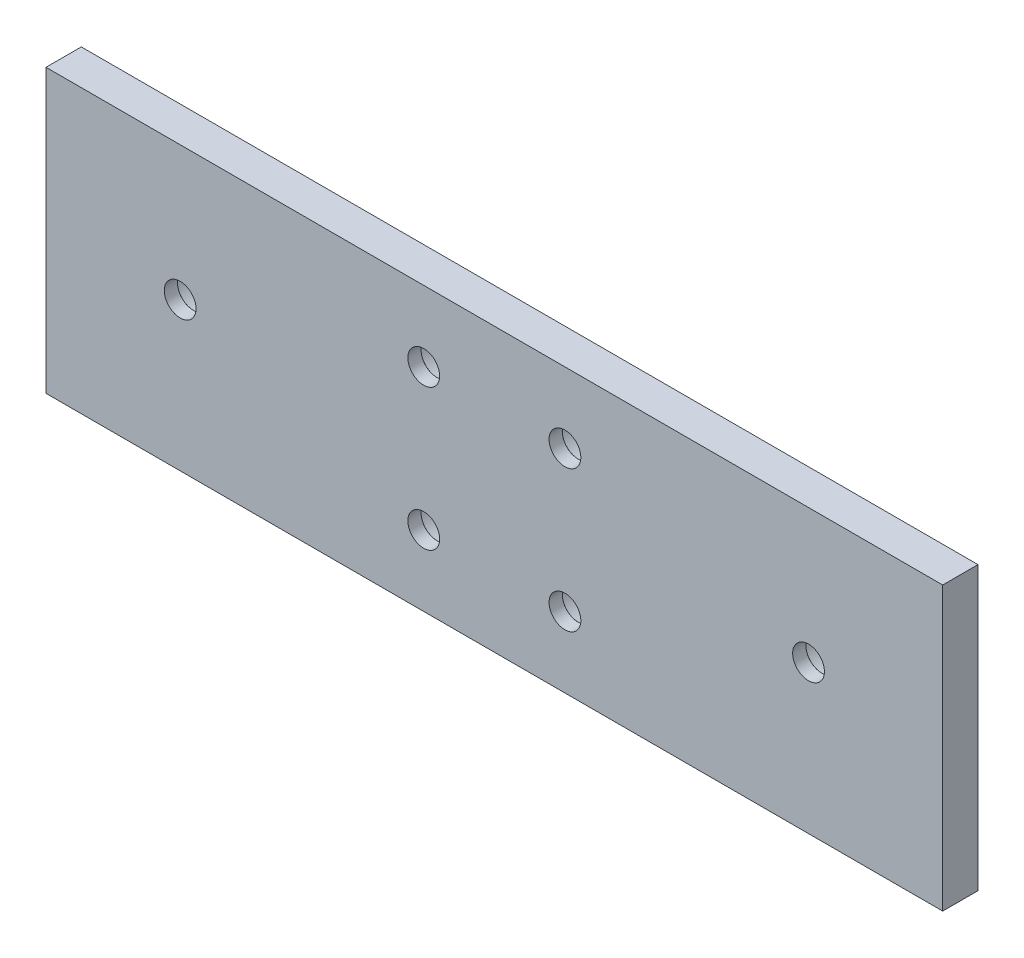
SolidWorks part; units mm, degrees
ref_plane "Plan de face" through (0, 0, 0) normal (0, 0, 1) x (1, 0, 0)
ref_plane "Plan de dessus" through (0, 0, 0) normal (0, 1, 0) x (1, 0, 0)
ref_plane "Plan de droite" through (0, 0, 0) normal (1, 0, 0) x (0, 0, -1)
sketch "Esquisse1" plane through (0, 0, 0) normal (0, 0, 1) x (1, 0, 0)
  line L1 (-63.5, -20) -> (63.5, -20)
  line L2 (-63.5, -20) -> (-63.5, 20)
  line L3 (-63.5, 20) -> (63.5, 20)
  line L4 (63.5, -20) -> (63.5, 20)
  line L5 (-63.5, -20) -> (63.5, 20) construction
  line L6 (-63.5, 20) -> (63.5, -20) construction
  point P0 (0, 0)
  dimension "D1" = 40
  dimension "D2" = 127
extrude "Boss.-Extru.1" add sketch "Esquisse1" along normal blind 5
hole_wizard "Chambrage pour vis à tête ronde bombée M41" positions "Esquisse3" profile "Esquisse2" counterbore size "M4" standard "Ansi Metric" end condition through all
sketch "Esquisse3" plane through (0, 0, 0) normal (0, 0, -1) x (-1, 0, 0)
  point P0 (-44.5, 1)
  point P3 (44.5, 1)
sketch "Esquisse2" plane through (44.5, 1, 0) normal (1, 0, 0) x (0, 1, 0)
  line L0 (0, 0) -> (0, 5)
  line L1 (0, 5) -> (2.25, 5)
  line L2 (2.25, 3.125) -> (2.25, 5)
  line L3 (2.25, 3.125) -> (2.275, 3.1)
  line L4 (2.275, 3.1) -> (4.5, 3.1)
  line L5 (4.5, 3.1) -> (4.5, 0)
  line L7 (0, 0) -> (4.5, 0)
  line L9 (-2.25, 3.125) -> (-2.275, 3.1) construction
  line L11 (0, -6.35) -> (0, 107.95) construction
  dimension "Diamètre du perçage jusqu'au prochain" = 4.5
  dimension "Profondeur du perçage jusqu'au prochain" = 5
  dimension "Diamètre du chambrage" = 9
  dimension "Profondeur du chambrage" = 3.1
  dimension "Diamètre du fraisage milieu" = 4.55
  dimension "Angle du fraisage milieu" = 90
hole_wizard "Dégagement M21" positions "Esquisse5" profile "Esquisse4" hole size "M2" standard "JIS" end condition through all
sketch "Esquisse5" plane through (0, 0, 5) normal (0, 0, 1) x (1, 0, 0)
  point P0 (10, -10)
  point P2 (10, 10)
  point P4 (-10, -10)
  point P6 (-10, 10)
sketch "Esquisse4" plane through (10, -10, 5) normal (1, 0, 0) x (0, -1, 0)
  line L0 (0, 0) -> (0, 5)
  line L1 (0, 5) -> (1.2, 5)
  line L2 (1.2, 5) -> (1.2, 0)
  line L5 (1.2, 0) -> (0, 0)
  line L11 (0, -6.35) -> (0, 107.95) construction
  dimension "Diamètre du perçage jusqu'au prochain" = 2.4
  dimension "Profondeur du perçage jusqu'au prochain" = 5
hole_wizard "Chambrage pour vis à tête ronde bombée M42" positions "Esquisse7" profile "Esquisse6" counterbore size "M4" standard "Ansi Metric" end condition through all
sketch "Esquisse7" plane through (0, 0, 0) normal (0, 0, -1) x (-1, 0, 0)
  point P0 (-10, -10)
  point P2 (-10, 10)
  point P4 (10, -10)
  point P6 (10, 10)
sketch "Esquisse6" plane through (10, -10, 0) normal (1, 0, 0) x (0, 1, 0)
  line L0 (0, 0) -> (0, 5)
  line L1 (0, 5) -> (2.25, 5)
  line L2 (2.25, 3.125) -> (2.25, 5)
  line L3 (2.25, 3.125) -> (2.275, 3.1)
  line L4 (2.275, 3.1) -> (4.5, 3.1)
  line L5 (4.5, 3.1) -> (4.5, 0)
  line L7 (0, 0) -> (4.5, 0)
  line L9 (-2.25, 3.125) -> (-2.275, 3.1) construction
  line L11 (0, -6.35) -> (0, 107.95) construction
  dimension "Diamètre du perçage jusqu'au prochain" = 4.5
  dimension "Profondeur du perçage jusqu'au prochain" = 5
  dimension "Diamètre du chambrage" = 9
  dimension "Profondeur du chambrage" = 3.1
  dimension "Diamètre du fraisage milieu" = 4.55
  dimension "Angle du fraisage milieu" = 90
